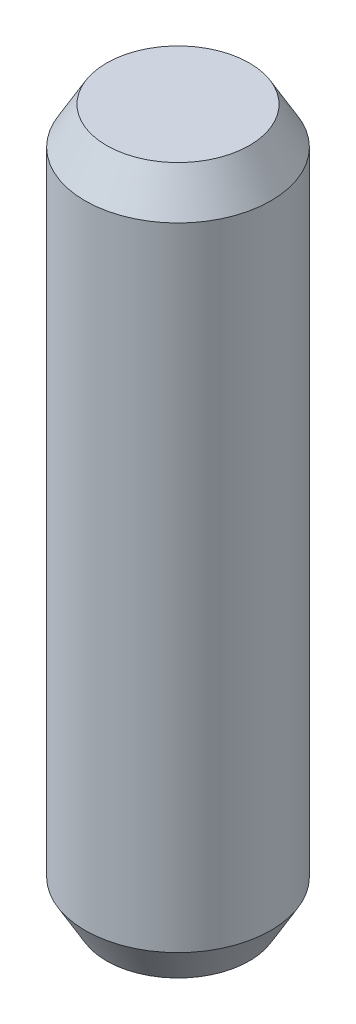
SolidWorks part; units mm, degrees
ref_plane "Front Plane" through (0, 0, 0) normal (0, 0, 1) x (1, 0, 0)
ref_plane "Top Plane" through (0, 0, 0) normal (0, 1, 0) x (1, 0, 0)
ref_plane "Right Plane" through (0, 0, 0) normal (1, 0, 0) x (0, 0, -1)
sketch "Sketch1" plane through (0, 0, 0) normal (0, 1, 0) x (1, 0, 0)
  circle A0 centre (0, 0) radius 3.175
  dimension "D1" = 6.35
extrude "Boss-Extrude1" add sketch "Sketch1" along normal blind 24.13
chamfer "Chamfer2" distance 1.27 angle 30 2 edges at (0, 0, 3.175) (0, 24.13, 3.175)
